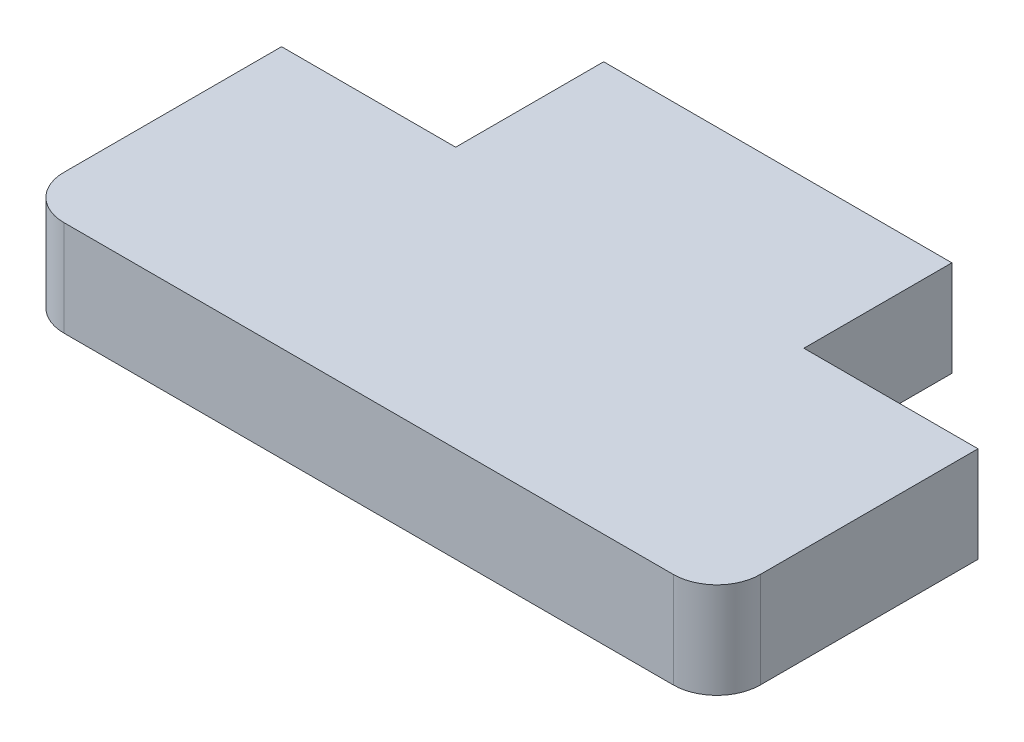
SolidWorks part; units mm, degrees
ref_plane "Front Plane" through (0, 0, 0) normal (0, 0, 1) x (1, 0, 0)
ref_plane "Top Plane" through (0, 0, 0) normal (0, 1, 0) x (1, 0, 0)
ref_plane "Right Plane" through (0, 0, 0) normal (1, 0, 0) x (0, 0, -1)
sketch "Sketch1" plane through (0, 0, 0) normal (0, 1, 0) x (1, 0, 0)
  line L0 (0, 0) -> (-10, 0)
  line L2 (0, 0) -> (0, 8.5)
  line L3 (0, 8.5) -> (20, 8.5)
  line L4 (20, 0) -> (20, 8.5)
  line L5 (30, 0) -> (20, 0)
  line L6 (30, 0) -> (30, -15)
  line L7 (30, -15) -> (-10, -15)
  line L8 (-10, 0) -> (-10, -15)
  dimension "D1" = 20
  dimension "D2" = 8.5
  dimension "D3" = 40
  dimension "D4" = 10
  dimension "D5" = 15
extrude "Boss-Extrude1" add sketch "Sketch1" along normal blind 5.5
fillet "Fillet1" radius 2.5 2 edges at (30, 2.75, 15) (-10, 2.75, 15)
